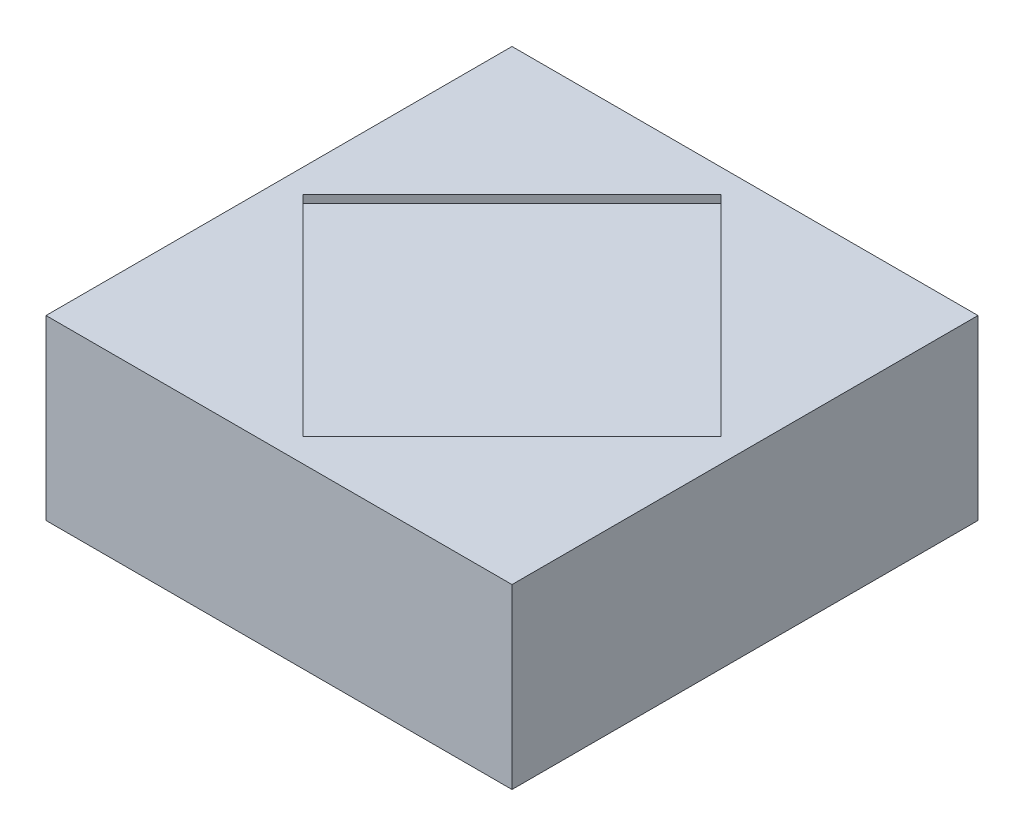
SolidWorks part; units mm, degrees
ref_plane "Front Plane" through (0, 0, 0) normal (0, 0, 1) x (1, 0, 0)
ref_plane "Top Plane" through (0, 0, 0) normal (0, 1, 0) x (1, 0, 0)
ref_plane "Right Plane" through (0, 0, 0) normal (1, 0, 0) x (0, 0, -1)
sketch "Sketch1" plane through (0, 0, 0) normal (0, 1, 0) x (1, 0, 0)
  line L1 (0, 0) -> (31.5, 0)
  line L2 (0, 0) -> (0, 31.5)
  line L3 (0, 31.5) -> (31.5, 31.5)
  line L4 (31.5, 0) -> (31.5, 31.5)
  dimension "D1" = 31.5
  dimension "D2" = 31.5
extrude "Boss-Extrude1" add sketch "Sketch1" along normal blind 12
sketch "Sketch3" plane through (0, 12, 0) normal (0, 1, 0) x (1, 0, 0)
  line L0 (0, 15.75) -> (31.5, 15.75) construction
  line L1 (0, 31.5) -> (0, 0) construction
  line L2 (31.5, 0) -> (31.5, 31.5) construction
  line L3 (15.75, 31.5) -> (15.75, 0) construction
  line L4 (31.5, 31.5) -> (0, 31.5) construction
  line L5 (0, 0) -> (31.5, 0) construction
  line L6 (1.6079, 15.75) -> (15.75, 1.6079)
  line L7 (1.6079, 15.75) -> (15.75, 29.8921)
  line L8 (15.75, 1.6079) -> (29.8921, 15.75)
  line L9 (15.75, 29.8921) -> (29.8921, 15.75)
  point P12 (0, 0)
  point P15 (0, 0)
  point P18 (2.1286, 15.75)
  dimension "D1" = 20
extrude "Cut-Extrude1" cut sketch "Sketch3" against normal blind 0.5
